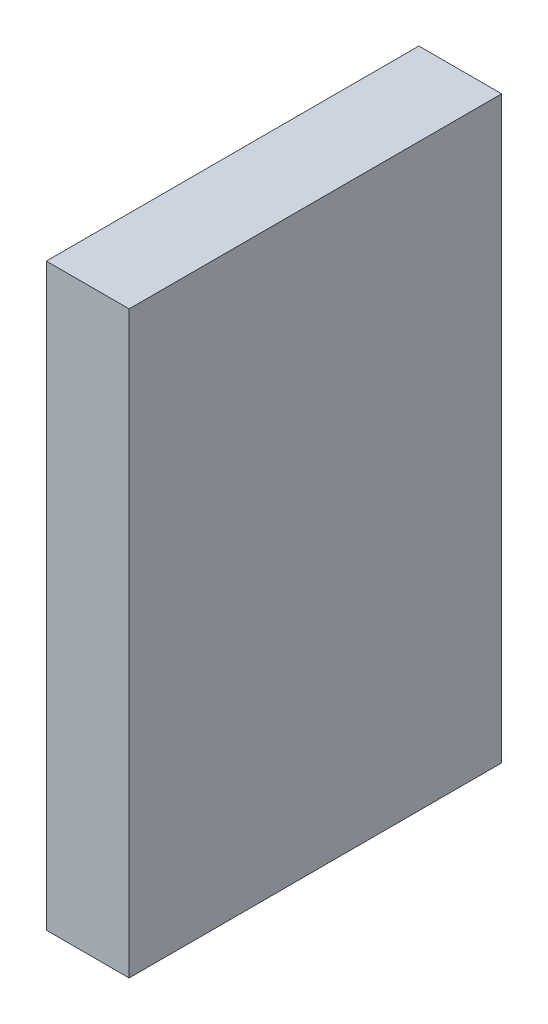
SolidWorks part; units mm, degrees
material "Maple"
ref_plane "Front Plane" through (0, 0, 0) normal (0, 0, 1) x (1, 0, 0)
ref_plane "Top Plane" through (0, 0, 0) normal (0, 1, 0) x (1, 0, 0)
ref_plane "Right Plane" through (0, 0, 0) normal (1, 0, 0) x (0, 0, -1)
sketch "Sketch1" plane through (0, 0, 0) normal (1, 0, 0) x (0, 0, -1)
  line L1 (22.5, 35) -> (-22.5, 35)
  line L2 (22.5, 35) -> (22.5, -35)
  line L3 (22.5, -35) -> (-22.5, -35)
  line L4 (-22.5, 35) -> (-22.5, -35)
  line L5 (22.5, 35) -> (-22.5, -35) construction
  line L6 (22.5, -35) -> (-22.5, 35) construction
  point P0 (0, 0)
  dimension "D1" = 45
  dimension "D2" = 70
extrude "Boss-Extrude1" add sketch "Sketch1" along normal blind 10
